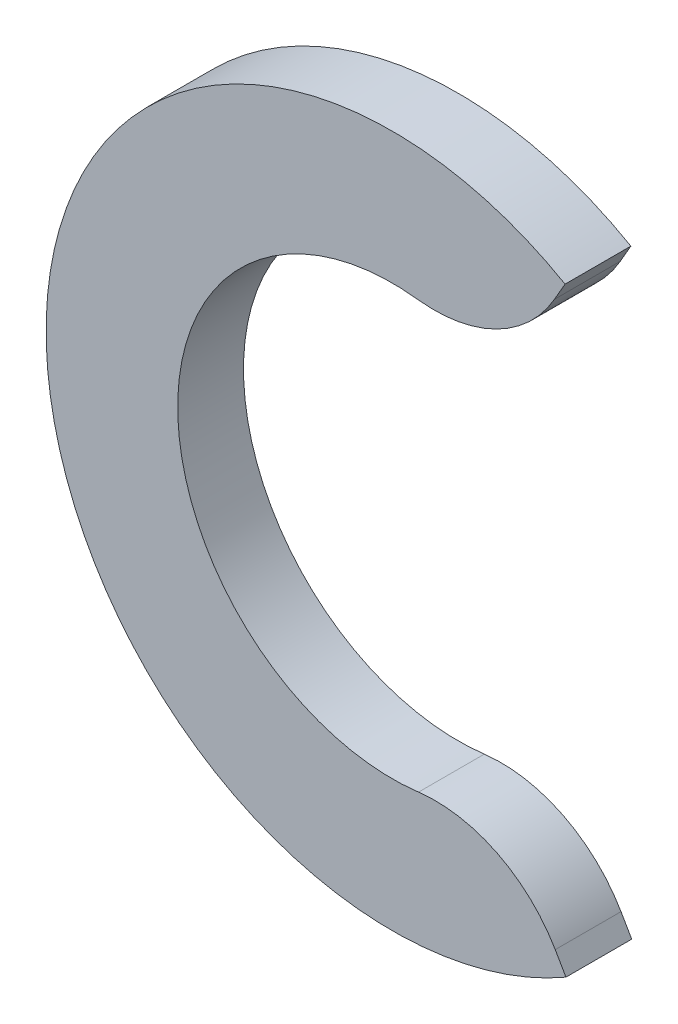
SolidWorks part; units mm, degrees
ref_plane "Front Plane" through (0, 0, 0) normal (0, 0, 1) x (1, 0, 0)
ref_plane "Top Plane" through (0, 0, 0) normal (0, 1, 0) x (1, 0, 0)
ref_plane "Right Plane" through (0, 0, 0) normal (1, 0, 0) x (0, 0, -1)
sketch "Sketch1" plane through (0, 0, 0) normal (0, 0, 1) x (1, 0, 0)
  line L2 (1.5461, 2.6869) -> (2.4937, 4.3338)
  line L3 (1.5539, -2.6824) -> (2.5063, -4.3265)
  arc A0 (1.5461, 2.6869) -> (1.5539, -2.6824) centre (0, 0) ccw
  arc A1 (2.4937, 4.3338) -> (2.5063, -4.3265) centre (0, 0) ccw
  dimension "D1" = 6.2
  dimension "D3" = 10
extrude "Boss-Extrude1" add sketch "Sketch1" along normal blind 0.95
fillet "Fillet1" radius 2 2 edges at (1.5539, -2.6824, 0.475) (1.5461, 2.6869, 0.475)
